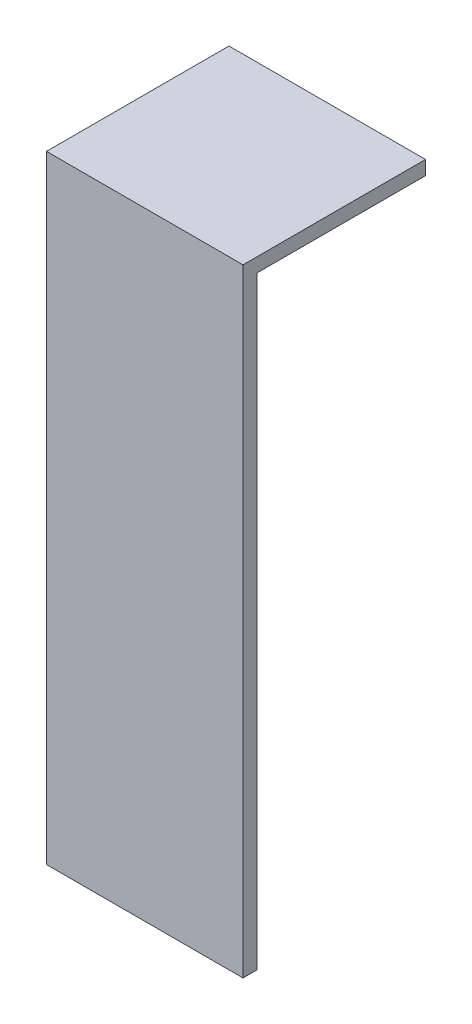
SolidWorks part; units mm, degrees
ref_plane "Front Plane" through (0, 0, 0) normal (0, 0, 1) x (1, 0, 0)
ref_plane "Top Plane" through (0, 0, 0) normal (0, 1, 0) x (1, 0, 0)
ref_plane "Right Plane" through (0, 0, 0) normal (1, 0, 0) x (0, 0, -1)
sketch "Sketch3" plane through (0, 0, 0) normal (0, 0, 1) x (1, 0, 0)
  line L0 (35.75, 0) -> (-35.75, 0) construction
  line L1 (-102.4311, 110) -> (-32.4311, 110)
  line L2 (-102.4311, 110) -> (-102.4311, -110)
  line L3 (-102.4311, -110) -> (-32.4311, -110)
  line L4 (-32.4311, 110) -> (-32.4311, -110)
  line L5 (-102.4311, 110) -> (-32.4311, -110) construction
  line L6 (-102.4311, -110) -> (-32.4311, 110) construction
  point P0 (-67.4311, 0)
  dimension "D1" = 70
  dimension "D2" = 220
extrude "Boss-Extrude2" add sketch "Sketch3" along normal blind 5
sketch "Sketch4" plane through (0, 0, 0) normal (0, 0, 1) x (1, 0, 0)
  line L1 (-102.4311, -110) -> (-97.4311, -110)
  line L2 (-102.4311, -110) -> (-102.4311, -10)
  line L3 (-102.4311, -10) -> (-97.4311, -10)
  line L4 (-97.4311, -110) -> (-97.4311, -10)
  dimension "D1" = 100
  dimension "D2" = 5
extrude "Boss-Extrude3" add sketch "Sketch4" against normal blind 10
sketch "Sketch5" plane through (0, 0, 0) normal (0, 0, 1) x (1, 0, 0)
  line L0 (-102.4311, 110) -> (-102.4311, -10) construction
  line L1 (-32.4311, 110) -> (-102.4311, 110)
  line L2 (-32.4311, 110) -> (-32.4311, 105)
  line L3 (-32.4311, 105) -> (-102.4311, 105)
  line L4 (-102.4311, 110) -> (-102.4311, 105)
  dimension "D1" = 5
extrude "Boss-Extrude4" add sketch "Sketch5" against normal blind 60
